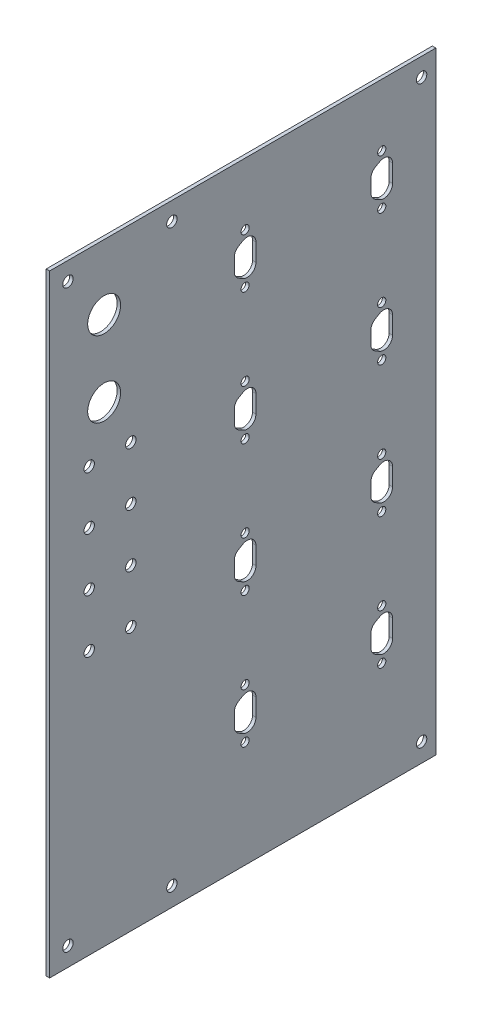
SolidWorks part; units mm, degrees
ref_plane "Plano frontal" through (0, 0, 0) normal (0, 0, 1) x (1, 0, 0)
ref_plane "Plano superior" through (0, 0, 0) normal (0, 1, 0) x (1, 0, 0)
ref_plane "Plano direito" through (0, 0, 0) normal (1, 0, 0) x (0, 0, -1)
sketch "Esboço1" plane through (0, 0, 0) normal (1, 0, 0) x (0, 0, -1)
  line L0 (-544.0743, -37.4447) -> (-430.7243, -37.4447)
  line L1 (-544.0743, -215.9947) -> (-430.7243, -215.9947)
  line L2 (-544.0743, -215.9947) -> (-544.0743, -37.4447)
  line L4 (-430.7243, -215.9947) -> (-430.7243, -37.4447)
  line L8 (-489.8353, -178.9325) -> (-489.8353, -175.2728)
  line L9 (-488.5803, -173.0991) -> (-487.3503, -172.389)
  line L10 (-483.5853, -179.6427) -> (-483.5853, -174.5627)
  line L11 (-487.3503, -181.8164) -> (-488.5803, -181.1063)
  line L15 (-487.3503, -143.9447) -> (-488.5803, -143.2346)
  line L16 (-489.8353, -141.0609) -> (-489.8353, -137.4012)
  line L17 (-488.5803, -135.2274) -> (-487.3503, -134.5173)
  line L18 (-483.5853, -136.691) -> (-483.5853, -141.771)
  line L19 (-488.5803, -105.3629) -> (-487.3503, -106.0731)
  line L20 (-483.5853, -103.8993) -> (-483.5853, -98.8193)
  line L21 (-487.3503, -96.6456) -> (-488.5803, -97.3558)
  line L22 (-489.8353, -99.5295) -> (-489.8353, -103.1892)
  line L23 (-489.8353, -65.3175) -> (-489.8353, -61.6578)
  line L24 (-488.5803, -59.4841) -> (-487.3503, -58.774)
  line L25 (-483.5853, -60.9477) -> (-483.5853, -66.0277)
  line L26 (-487.3503, -68.2014) -> (-488.5803, -67.4913)
  line L27 (-447.9593, -68.2014) -> (-449.1893, -67.4913)
  line L28 (-450.4443, -65.3175) -> (-450.4443, -61.6578)
  line L29 (-449.1893, -59.4841) -> (-447.9593, -58.774)
  line L30 (-444.1943, -60.9477) -> (-444.1943, -66.0277)
  line L31 (-450.4443, -103.1892) -> (-450.4443, -99.5295)
  line L32 (-449.1893, -97.3558) -> (-447.9593, -96.6456)
  line L33 (-444.1943, -98.8193) -> (-444.1943, -103.8993)
  line L34 (-447.9593, -106.0731) -> (-449.1893, -105.3629)
  line L35 (-449.1893, -143.2346) -> (-447.9593, -143.9447)
  line L36 (-447.9593, -143.9447) -> (-447.9301, -143.9397)
  line L37 (-444.1943, -141.771) -> (-444.1943, -136.691)
  line L38 (-447.9593, -134.5173) -> (-449.1893, -135.2274)
  line L39 (-450.4443, -137.4012) -> (-450.4443, -141.0609)
  line L40 (-450.4443, -178.9325) -> (-450.4443, -175.2728)
  line L41 (-449.1893, -173.0991) -> (-447.9593, -172.389)
  line L42 (-444.1943, -174.5627) -> (-444.1943, -179.6427)
  line L43 (-447.9593, -181.8164) -> (-449.1893, -181.1063)
  circle A0 centre (-507.8243, -209.5847) radius 1.5
  circle A1 centre (-537.7963, -209.5847) radius 1.5
  circle A3 centre (-537.7963, -43.7227) radius 1.5
  circle A4 centre (-507.8243, -43.7227) radius 1.5
  circle A5 centre (-486.7103, -56.3127) radius 1.18
  circle A6 centre (-486.7103, -70.6627) radius 1.18
  circle A7 centre (-447.3193, -70.6627) radius 1.18
  circle A8 centre (-447.3193, -56.3127) radius 1.18
  circle A9 centre (-447.3193, -94.1843) radius 1.18
  circle A10 centre (-447.3193, -132.056) radius 1.18
  circle A11 centre (-447.3193, -108.5343) radius 1.18
  circle A12 centre (-447.3193, -146.406) radius 1.18
  circle A13 centre (-447.3193, -184.2777) radius 1.18
  circle A14 centre (-447.3193, -169.9277) radius 1.18
  circle A15 centre (-486.7103, -184.2777) radius 1.18
  circle A16 centre (-486.7103, -169.9277) radius 1.18
  circle A17 centre (-486.7103, -146.406) radius 1.18
  circle A18 centre (-486.7103, -132.056) radius 1.18
  circle A19 centre (-486.7103, -94.1843) radius 1.18
  circle A20 centre (-486.7103, -108.5343) radius 1.18
  circle A21 centre (-527.3569, -79.0287) radius 4.75
  circle A22 centre (-527.3569, -57.2101) radius 4.75
  circle A23 centre (-531.6683, -139.0439) radius 1.5
  circle A24 centre (-531.6683, -123.6769) radius 1.5
  circle A25 centre (-531.6683, -108.3099) radius 1.5
  circle A26 centre (-531.6683, -92.9429) radius 1.5
  circle A27 centre (-519.6683, -92.9429) radius 1.5
  circle A28 centre (-519.6683, -108.3099) radius 1.5
  circle A29 centre (-519.6683, -123.6769) radius 1.5
  circle A30 centre (-519.6683, -139.0439) radius 1.5
  arc A33 (-488.5803, -181.1063) -> (-489.8353, -178.9325) centre (-487.3253, -178.9325) cw
  arc A34 (-489.8353, -175.2728) -> (-488.5803, -173.0991) centre (-487.3253, -175.2728) cw
  arc A36 (-483.5853, -174.5627) -> (-487.3503, -172.389) centre (-486.0953, -174.5627) ccw
  arc A37 (-487.3503, -181.8164) -> (-483.5853, -179.6427) centre (-486.0953, -179.6427) ccw
  arc A38 (-487.3503, -143.9447) -> (-483.5853, -141.771) centre (-486.0953, -141.771) ccw
  arc A39 (-483.5853, -136.691) -> (-487.3503, -134.5173) centre (-486.0953, -136.691) ccw
  arc A40 (-488.5803, -143.2346) -> (-489.8353, -141.0609) centre (-487.3253, -141.0609) cw
  arc A41 (-489.8353, -137.4012) -> (-488.5803, -135.2274) centre (-487.3253, -137.4012) cw
  arc A42 (-487.3503, -106.0731) -> (-483.5853, -103.8993) centre (-486.0953, -103.8993) ccw
  arc A43 (-483.5853, -98.8193) -> (-487.3503, -96.6456) centre (-486.0953, -98.8193) ccw
  arc A45 (-488.5803, -105.3629) -> (-489.8353, -103.1892) centre (-487.3253, -103.1892) cw
  arc A46 (-489.8353, -99.5295) -> (-488.5803, -97.3558) centre (-487.3253, -99.5295) cw
  arc A48 (-488.5803, -67.4913) -> (-489.8353, -65.3175) centre (-487.3253, -65.3175) cw
  arc A49 (-489.8353, -61.6578) -> (-488.5803, -59.4841) centre (-487.3253, -61.6578) cw
  arc A50 (-487.3503, -58.774) -> (-483.5853, -60.9477) centre (-486.0953, -60.9477) cw
  arc A51 (-483.5853, -66.0277) -> (-487.3503, -68.2014) centre (-486.0953, -66.0277) cw
  arc A52 (-447.9593, -68.2014) -> (-444.1943, -66.0277) centre (-446.7043, -66.0277) ccw
  arc A53 (-444.1943, -60.9477) -> (-447.9593, -58.774) centre (-446.7043, -60.9477) ccw
  arc A54 (-449.1893, -67.4913) -> (-450.4443, -65.3175) centre (-447.9343, -65.3175) cw
  arc A55 (-450.4443, -61.6578) -> (-449.1893, -59.4841) centre (-447.9343, -61.6578) cw
  arc A57 (-449.1893, -105.3629) -> (-450.4443, -103.1892) centre (-447.9343, -103.1892) cw
  arc A58 (-450.4443, -99.5295) -> (-449.1893, -97.3558) centre (-447.9343, -99.5295) cw
  arc A59 (-447.9593, -96.6456) -> (-444.1943, -98.8193) centre (-446.7043, -98.8193) cw
  arc A61 (-444.1943, -103.8993) -> (-447.9593, -106.0731) centre (-446.7043, -103.8993) cw
  arc A62 (-447.9593, -143.9447) -> (-444.1943, -141.771) centre (-446.7043, -141.771) ccw
  arc A63 (-444.1943, -136.691) -> (-447.9593, -134.5173) centre (-446.7043, -136.691) ccw
  arc A64 (-449.1893, -135.2274) -> (-450.4443, -137.4012) centre (-447.9343, -137.4012) ccw
  arc A65 (-450.4443, -141.0609) -> (-449.1893, -143.2346) centre (-447.9343, -141.0609) ccw
  arc A66 (-449.1893, -181.1063) -> (-450.4443, -178.9325) centre (-447.9343, -178.9325) cw
  arc A67 (-450.4443, -175.2728) -> (-449.1893, -173.0991) centre (-447.9343, -175.2728) cw
  arc A68 (-447.9593, -172.389) -> (-444.1943, -174.5627) centre (-446.7043, -174.5627) cw
  arc A69 (-444.1943, -179.6427) -> (-447.9593, -181.8164) centre (-446.7043, -179.6427) cw
  circle A70 centre (-435.8243, -209.5847) radius 1.5
  circle A71 centre (-435.8243, -43.7227) radius 1.5
  dimension "D6" = 72
  dimension "D7" = 72
extrude "Ressalto-extrusão2" add sketch "Esboço1" along normal blind 1 separate body contours L1 L4 L0 L2 A71 A70 L33 A61 L34 A57 L31 A58 L32 A59 L25 A51 L26 A48 L23 A49 L24 A50 L16 A41 L17 A39 L18 A38 L15 A40 A37 L11 A33 L8 A34 L9 A36 L10 A30 A29 A28
sketch "Esboço2" plane through (1, 0, 0) normal (1, 0, 0) x (0, 0, -1)
  line L0 (-544.0743, -215.9947) -> (-430.7243, -215.9947) construction
  line L1 (-543.0743, -214.9947) -> (-431.7243, -214.9947)
  line L2 (-543.0743, -214.9947) -> (-543.0743, -38.4447)
  line L3 (-543.0743, -38.4447) -> (-431.7243, -38.4447)
  line L4 (-431.7243, -214.9947) -> (-431.7243, -38.4447)
  line L5 (-544.0743, -37.4447) -> (-430.7243, -37.4447) construction
  line L6 (-544.0743, -215.9947) -> (-544.0743, -37.4447) construction
  line L7 (-430.7243, -215.9947) -> (-430.7243, -37.4447) construction
  line L9 (-544.0743, -215.9947) -> (-430.7243, -215.9947)
  line L10 (-544.0743, -215.9947) -> (-544.0743, -37.4447)
  line L11 (-544.0743, -37.4447) -> (-430.7243, -37.4447)
  line L12 (-430.7243, -215.9947) -> (-430.7243, -37.4447)
  dimension "D1" = 1
  dimension "D2" = 1
  dimension "D3" = 1
  dimension "D4" = 1
extrude "Corte-extrusão1" cut sketch "Esboço2" against normal through all
